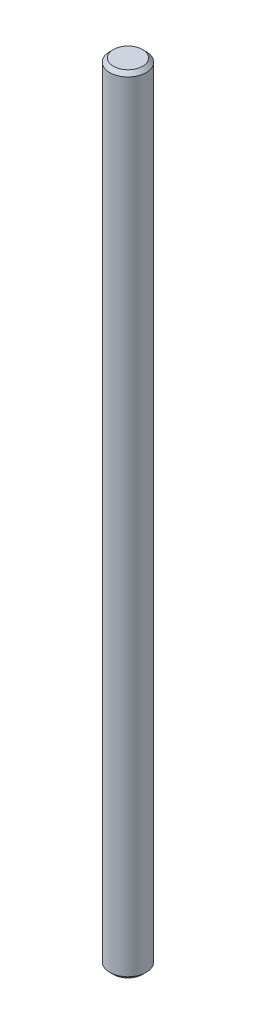
SolidWorks part; units mm, degrees
ref_plane "前视基准面" through (0, 0, 0) normal (0, 0, 1) x (1, 0, 0)
ref_plane "上视基准面" through (0, 0, 0) normal (0, 1, 0) x (1, 0, 0)
ref_plane "右视基准面" through (0, 0, 0) normal (1, 0, 0) x (0, 0, -1)
other "Configuration Table"
sketch "草图1" plane through (0, 0, 0) normal (0, 1, 0) x (1, 0, 0)
  circle A0 centre (0, 0) radius 2.5
  dimension "D1" = 5
extrude "凸台-拉伸1" add sketch "草图1" along normal blind 108
chamfer "倒角1" distance 0.5 angle 45 2 edges at (0, 0, 2.5) (0, 108, 2.5)
